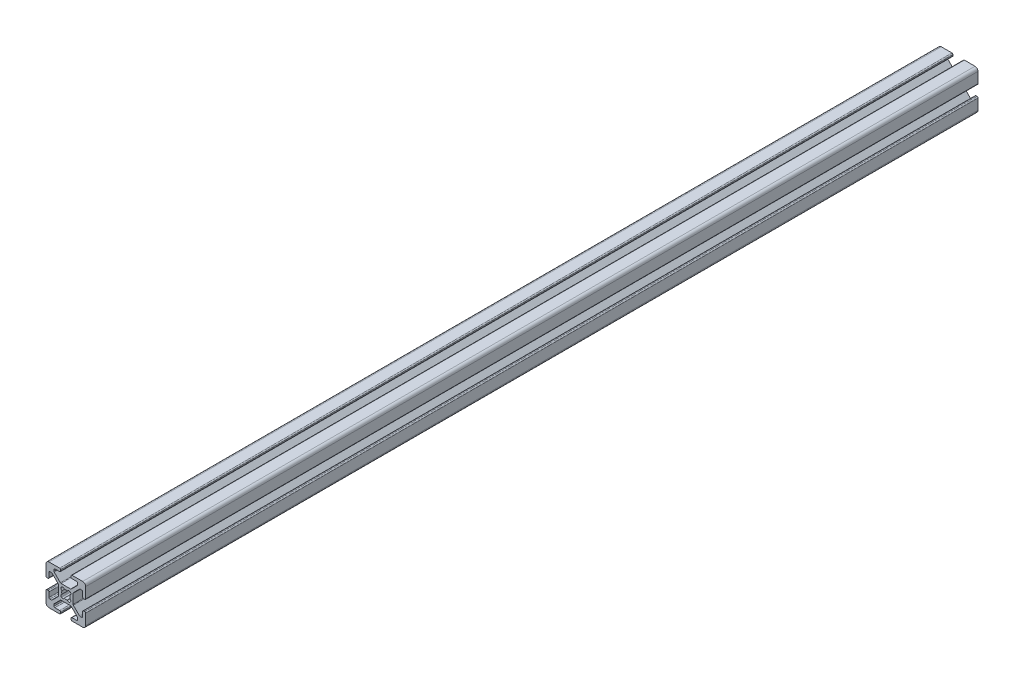
SolidWorks part; units mm, degrees
ref_plane "Front Plane" through (0, 0, 0) normal (0, 0, 1) x (1, 0, 0)
ref_plane "Top Plane" through (0, 0, 0) normal (0, 1, 0) x (1, 0, 0)
ref_plane "Right Plane" through (0, 0, 0) normal (1, 0, 0) x (0, 0, -1)
sketch "Sketch1" plane through (0, 0, 0) normal (0, 0, 1) x (1, 0, 0)
  line L0 (-5.0323, -0.3411) -> (-5.5163, -0.3411)
  line L1 (-6.0243, 0.1669) -> (-6.0243, 2.5159)
  line L2 (-4.5243, 0.1669) -> (-4.5243, 5.5289)
  line L3 (-10.8693, -5.355) -> (-10.8693, -0.5871)
  line L4 (-7.2582, 3.0239) -> (-6.5323, 3.0239)
  line L5 (-7.6174, 2.8752) -> (-10.7205, -0.2279)
  line L6 (-5.0323, -5.6011) -> (-5.5163, -5.6011)
  line L7 (-4.5243, -6.1091) -> (-4.5243, -11.4711)
  line L8 (-6.0243, -6.1091) -> (-6.0243, -8.4581)
  line L9 (-7.2582, -8.9661) -> (-6.5323, -8.9661)
  line L10 (-7.6174, -8.8173) -> (-10.7205, -5.7142)
  line L11 (-12.3994, -5.2756) -> (-12.2198, -5.096)
  line L12 (-17.1543, 6.5209) -> (-17.1543, 6.0369)
  line L13 (-17.6623, 7.0289) -> (-23.0243, 7.0289)
  line L14 (-17.6623, 5.5289) -> (-20.0113, 5.5289)
  line L15 (-12.1404, 0.6839) -> (-16.9082, 0.6839)
  line L16 (-20.5193, 4.295) -> (-20.5193, 5.0209)
  line L17 (-20.3705, 3.9358) -> (-17.2674, 0.8327)
  line L18 (-11.8943, 6.5209) -> (-11.8943, 6.0369)
  line L19 (-11.3863, 7.0289) -> (-6.0243, 7.0289)
  line L20 (-11.3863, 5.5289) -> (-9.0373, 5.5289)
  line L21 (-8.5293, 4.295) -> (-8.5293, 5.0209)
  line L22 (-8.6781, 3.9358) -> (-11.7812, 0.8327)
  line L23 (-12.2198, -0.8462) -> (-12.3994, -0.6666)
  line L24 (-24.0163, -5.6011) -> (-23.5323, -5.6011)
  line L25 (-24.5243, -6.1091) -> (-24.5243, -11.4711)
  line L26 (-23.0243, -6.1091) -> (-23.0243, -8.4581)
  line L27 (-18.1793, -0.5871) -> (-18.1793, -5.355)
  line L28 (-21.7904, -8.9661) -> (-22.5163, -8.9661)
  line L29 (-21.4312, -8.8173) -> (-18.3281, -5.7142)
  line L30 (-24.0163, -0.3411) -> (-23.5323, -0.3411)
  line L31 (-24.5243, 0.1669) -> (-24.5243, 5.5289)
  line L32 (-23.0243, 0.1669) -> (-23.0243, 2.5159)
  line L33 (-21.7904, 3.0239) -> (-22.5163, 3.0239)
  line L34 (-21.4312, 2.8752) -> (-18.3281, -0.2279)
  line L35 (-16.6492, -0.6666) -> (-16.8288, -0.8462)
  line L36 (-11.8943, -12.4631) -> (-11.8943, -11.9791)
  line L37 (-11.3863, -12.9711) -> (-6.0243, -12.9711)
  line L38 (-11.3863, -11.4711) -> (-9.0373, -11.4711)
  line L39 (-16.9082, -6.6261) -> (-12.1404, -6.6261)
  line L40 (-8.5293, -10.2371) -> (-8.5293, -10.9631)
  line L41 (-8.6781, -9.8779) -> (-11.7812, -6.7748)
  line L42 (-17.1543, -12.4631) -> (-17.1543, -11.9791)
  line L43 (-17.6623, -12.9711) -> (-23.0243, -12.9711)
  line L44 (-17.6623, -11.4711) -> (-20.0113, -11.4711)
  line L45 (-20.5193, -10.2371) -> (-20.5193, -10.9631)
  line L46 (-20.3705, -9.8779) -> (-17.2674, -6.7748)
  line L47 (-16.8288, -5.096) -> (-16.6492, -5.2756)
  arc A0 (-15.3283, -4.9062) -> (-13.7203, -4.9062) centre (-14.5243, -2.9711) ccw
  arc A1 (-6.0243, 2.5159) -> (-6.5323, 3.0239) centre (-6.5323, 2.5159) ccw
  arc A2 (-7.2582, 3.0239) -> (-7.6174, 2.8752) centre (-7.2582, 2.5159) ccw
  arc A3 (-10.7205, -0.2279) -> (-10.8693, -0.5871) centre (-10.3613, -0.5871) ccw
  arc A4 (-10.8693, -5.355) -> (-10.7205, -5.7142) centre (-10.3613, -5.355) ccw
  arc A5 (-7.6174, -8.8173) -> (-7.2582, -8.9661) centre (-7.2582, -8.4581) ccw
  arc A6 (-6.5323, -8.9661) -> (-6.0243, -8.4581) centre (-6.5323, -8.4581) ccw
  arc A7 (-5.5163, -5.6011) -> (-6.0243, -6.1091) centre (-5.5163, -6.1091) ccw
  arc A8 (-4.5243, -6.1091) -> (-5.0323, -5.6011) centre (-5.0323, -6.1091) ccw
  arc A9 (-5.0323, -0.3411) -> (-4.5243, 0.1669) centre (-5.0323, 0.1669) ccw
  arc A10 (-6.0243, 0.1669) -> (-5.5163, -0.3411) centre (-5.5163, 0.1669) ccw
  arc A11 (-13.7203, -4.9062) -> (-12.3994, -5.2756) centre (-12.9559, -4.7191) ccw
  arc A12 (-12.2198, -5.096) -> (-12.5892, -3.775) centre (-12.7763, -4.5395) ccw
  arc A13 (-17.1543, 6.5209) -> (-17.6623, 7.0289) centre (-17.6623, 6.5209) ccw
  arc A14 (-17.6623, 5.5289) -> (-17.1543, 6.0369) centre (-17.6623, 6.0369) ccw
  arc A15 (-12.5892, -3.775) -> (-12.5892, -2.1671) centre (-14.5243, -2.9711) ccw
  arc A16 (-17.2674, 0.8327) -> (-16.9082, 0.6839) centre (-16.9082, 1.1919) ccw
  arc A17 (-20.0113, 5.5289) -> (-20.5193, 5.0209) centre (-20.0113, 5.0209) ccw
  arc A18 (-20.5193, 4.295) -> (-20.3705, 3.9358) centre (-20.0113, 4.295) ccw
  arc A19 (-11.8943, 6.0369) -> (-11.3863, 5.5289) centre (-11.3863, 6.0369) ccw
  arc A20 (-11.3863, 7.0289) -> (-11.8943, 6.5209) centre (-11.3863, 6.5209) ccw
  arc A21 (-8.5293, 5.0209) -> (-9.0373, 5.5289) centre (-9.0373, 5.0209) ccw
  arc A22 (-8.6781, 3.9358) -> (-8.5293, 4.295) centre (-9.0373, 4.295) ccw
  arc A23 (-12.1404, 0.6839) -> (-11.7812, 0.8327) centre (-12.1404, 1.1919) ccw
  arc A24 (-12.5892, -2.1671) -> (-12.2198, -0.8462) centre (-12.7763, -1.4027) ccw
  arc A25 (-12.3994, -0.6666) -> (-13.7203, -1.0359) centre (-12.9559, -1.223) ccw
  arc A26 (-24.0163, -5.6011) -> (-24.5243, -6.1091) centre (-24.0163, -6.1091) ccw
  arc A27 (-23.0243, -6.1091) -> (-23.5323, -5.6011) centre (-23.5323, -6.1091) ccw
  arc A28 (-13.7203, -1.0359) -> (-15.3283, -1.0359) centre (-14.5243, -2.9711) ccw
  arc A29 (-18.3281, -5.7142) -> (-18.1793, -5.355) centre (-18.6873, -5.355) ccw
  arc A30 (-23.0243, -8.4581) -> (-22.5163, -8.9661) centre (-22.5163, -8.4581) ccw
  arc A31 (-21.7904, -8.9661) -> (-21.4312, -8.8173) centre (-21.7904, -8.4581) ccw
  arc A32 (-23.5323, -0.3411) -> (-23.0243, 0.1669) centre (-23.5323, 0.1669) ccw
  arc A33 (-24.5243, 0.1669) -> (-24.0163, -0.3411) centre (-24.0163, 0.1669) ccw
  arc A34 (-22.5163, 3.0239) -> (-23.0243, 2.5159) centre (-22.5163, 2.5159) ccw
  arc A35 (-21.4312, 2.8752) -> (-21.7904, 3.0239) centre (-21.7904, 2.5159) ccw
  arc A36 (-18.1793, -0.5871) -> (-18.3281, -0.2279) centre (-18.6873, -0.5871) ccw
  arc A37 (-15.3283, -1.0359) -> (-16.6492, -0.6666) centre (-16.0927, -1.223) ccw
  arc A38 (-16.8288, -0.8462) -> (-16.4594, -2.1671) centre (-16.2723, -1.4027) ccw
  arc A39 (-11.8943, -12.4631) -> (-11.3863, -12.9711) centre (-11.3863, -12.4631) ccw
  arc A40 (-11.3863, -11.4711) -> (-11.8943, -11.9791) centre (-11.3863, -11.9791) ccw
  arc A41 (-16.4594, -2.1671) -> (-16.4594, -3.775) centre (-14.5243, -2.9711) ccw
  arc A42 (-11.7812, -6.7748) -> (-12.1404, -6.6261) centre (-12.1404, -7.1341) ccw
  arc A43 (-9.0373, -11.4711) -> (-8.5293, -10.9631) centre (-9.0373, -10.9631) ccw
  arc A44 (-8.5293, -10.2371) -> (-8.6781, -9.8779) centre (-9.0373, -10.2371) ccw
  arc A45 (-17.1543, -11.9791) -> (-17.6623, -11.4711) centre (-17.6623, -11.9791) ccw
  arc A46 (-17.6623, -12.9711) -> (-17.1543, -12.4631) centre (-17.6623, -12.4631) ccw
  arc A47 (-20.5193, -10.9631) -> (-20.0113, -11.4711) centre (-20.0113, -10.9631) ccw
  arc A48 (-20.3705, -9.8779) -> (-20.5193, -10.2371) centre (-20.0113, -10.2371) ccw
  arc A49 (-16.9082, -6.6261) -> (-17.2674, -6.7748) centre (-16.9082, -7.1341) ccw
  arc A50 (-16.4594, -3.775) -> (-16.8288, -5.096) centre (-16.2723, -4.5395) ccw
  arc A51 (-16.6492, -5.2756) -> (-15.3283, -4.9062) centre (-16.0927, -4.7191) ccw
  arc A52 (-4.5243, 5.5289) -> (-6.0243, 7.0289) centre (-6.0243, 5.5289) ccw
  arc A53 (-6.0243, -12.9711) -> (-4.5243, -11.4711) centre (-6.0243, -11.4711) ccw
  arc A54 (-24.5243, -11.4711) -> (-23.0243, -12.9711) centre (-23.0243, -11.4711) ccw
  arc A55 (-23.0243, 7.0289) -> (-24.5243, 5.5289) centre (-23.0243, 5.5289) ccw
extrude "Extrude1" add sketch "Sketch1" along normal blind 450
